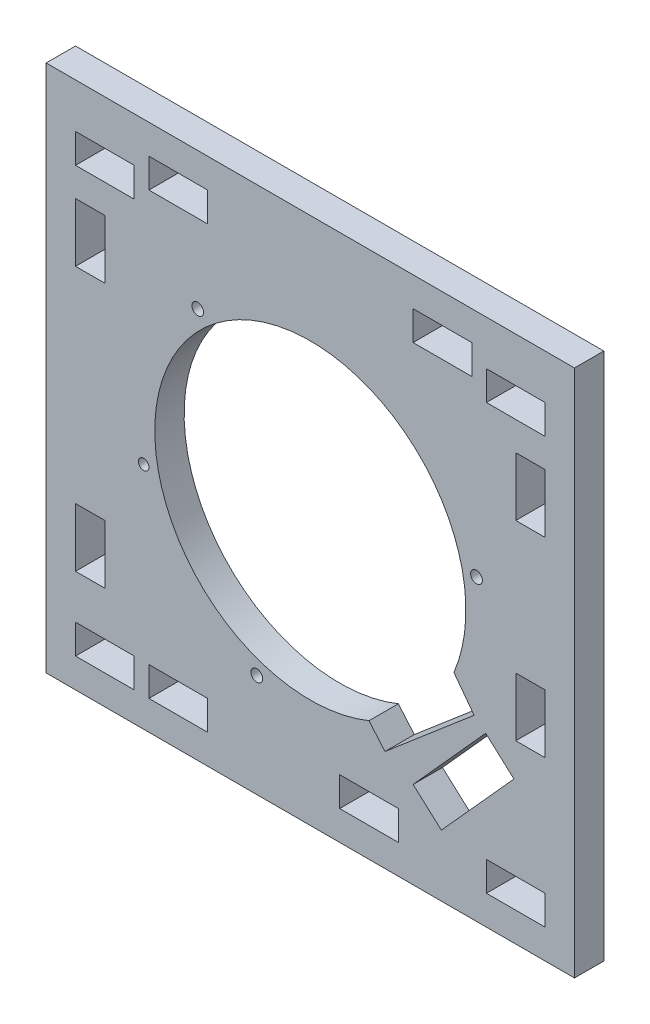
SolidWorks part; units mm, degrees
material "Balsa"
ref_plane "Plan de face" through (0, 0, 0) normal (0, 0, 1) x (1, 0, 0)
ref_plane "Plan de dessus" through (0, 0, 0) normal (0, 1, 0) x (1, 0, 0)
ref_plane "Plan de droite" through (0, 0, 0) normal (1, 0, 0) x (0, 0, -1)
sketch "Esquisse1" plane through (0, 0, 0) normal (0, 0, 1) x (1, 0, 0)
  line L0 (49.998, 15.0584) -> (52.714, 11.8706)
  line L1 (85, -5.4) -> (-5, -5.4)
  line L2 (85, -5.4) -> (85, 84.6)
  line L3 (85, 84.6) -> (-5, 84.6)
  line L4 (-5, -5.4) -> (-5, 84.6)
  line L6 (52.714, 11.8706) -> (67.9025, 24.8114)
  line L7 (67.9025, 24.8114) -> (64.4619, 29.4085)
  line L9 (57.5073, 9.4088) -> (69.8732, 23.1425)
  line L10 (69.8732, 23.1425) -> (74.6891, 18.8062)
  line L11 (74.6891, 18.8062) -> (62.3232, 5.0726)
  line L12 (62.3232, 5.0726) -> (57.5073, 9.4088)
  arc A0 (49.998, 15.0584) -> (64.4619, 29.4085) centre (40, 39.6) cw
  circle A1 centre (20.8169, 61.2152) radius 1
  circle A2 centre (68.3109, 45.4055) radius 1
  circle A3 centre (30.8722, 12.1793) radius 1
  circle A4 centre (11.6112, 33.6773) radius 0.9
  dimension "D1" = 90
  dimension "D2" = 90
  dimension "D5" = 26.5
  dimension "D3" = 45
  dimension "D4" = 45
extrude "Boss.-Extru.2" add sketch "Esquisse1" along normal blind 5
sketch "Esquisse2" plane through (0, 0, 0) normal (0, 0, -1) x (-1, 0, 0)
  line L0 (-40, 84.6) -> (-40, -5.4) construction
  line L1 (-80, 77) -> (-70, 77)
  line L2 (-80, 77) -> (-80, 72)
  line L3 (-80, 72) -> (-70, 72)
  line L4 (-70, 77) -> (-70, 72)
  line L5 (-10, 77) -> (-10, 72)
  line L6 (0, 72) -> (-10, 72)
  line L7 (0, 77) -> (0, 72)
  line L8 (0, 77) -> (-10, 77)
  line L9 (-85, 84.6) -> (5, 84.6) construction
  line L10 (5, -5.4) -> (-85, -5.4) construction
  line L11 (5, 39.6) -> (-85, 39.6) construction
  line L12 (5, 84.6) -> (5, -5.4) construction
  line L13 (-85, -5.4) -> (-85, 84.6) construction
  line L14 (-22.5, 74.6) -> (-22.5, 79.6)
  line L15 (-80, -0.4) -> (-70, -0.4)
  line L16 (-80, -0.4) -> (-80, 4.6)
  line L17 (-80, 4.6) -> (-70, 4.6)
  line L18 (-70, -0.4) -> (-70, 4.6)
  line L19 (-10, 4.6) -> (0, 4.6)
  line L20 (-10, 4.6) -> (-10, -0.4)
  line L21 (-10, -0.4) -> (0, -0.4)
  line L22 (0, 4.6) -> (0, -0.4)
  line L23 (-67.5, 74.6) -> (-57.5, 74.6)
  line L24 (-67.5, 74.6) -> (-67.5, 79.6)
  line L25 (-67.5, 79.6) -> (-57.5, 79.6)
  line L26 (-57.5, 74.6) -> (-57.5, 79.6)
  line L27 (-12.5, 79.6) -> (-22.5, 79.6)
  line L28 (-12.5, 74.6) -> (-12.5, 79.6)
  line L29 (-12.5, 74.6) -> (-22.5, 74.6)
  line L30 (-85, 84.6) -> (5, 84.6) construction
  line L31 (-5, 12.1) -> (-5, 22.1)
  line L32 (0, 67.1) -> (-5, 67.1)
  line L33 (0, 67.1) -> (0, 57.1)
  line L34 (0, 57.1) -> (-5, 57.1)
  line L35 (-5, 67.1) -> (-5, 57.1)
  line L36 (0, 22.1) -> (-5, 22.1)
  line L37 (0, 12.1) -> (0, 22.1)
  line L38 (0, 12.1) -> (-5, 12.1)
  line L39 (5, 84.6) -> (5, -5.4) construction
  line L40 (5, -5.4) -> (-85, -5.4) construction
  line L41 (-22.5, -0.4) -> (-12.5, -0.4)
  line L42 (-22.5, -0.4) -> (-22.5, 4.6)
  line L43 (-22.5, 4.6) -> (-12.5, 4.6)
  line L44 (-12.5, -0.4) -> (-12.5, 4.6)
  line L45 (-55, -0.4) -> (-45, -0.4)
  line L46 (-55, -0.4) -> (-55, 4.6)
  line L47 (-55, 4.6) -> (-45, 4.6)
  line L48 (-45, -0.4) -> (-45, 4.6)
  line L49 (-85, -5.4) -> (-85, 84.6) construction
  line L50 (-80, 57.1) -> (-75, 57.1)
  line L51 (-80, 57.1) -> (-80, 67.1)
  line L52 (-80, 67.1) -> (-75, 67.1)
  line L53 (-75, 57.1) -> (-75, 67.1)
  line L54 (-80, 34.6) -> (-75, 34.6)
  line L55 (-80, 34.6) -> (-80, 24.6)
  line L56 (-80, 24.6) -> (-75, 24.6)
  line L57 (-75, 34.6) -> (-75, 24.6)
  circle A4 centre (-40, 39.6) radius 40 construction
  dimension "D15" = 10
  dimension "D18" = 5
  dimension "D20" = 35
  dimension "D22" = 80
  dimension "D24" = 10
  dimension "D25" = 5
  dimension "D26" = 17.5
  dimension "D28" = 5
  dimension "D29" = 5
  dimension "D1" = 60
  dimension "D2" = 10
  dimension "D3" = 5
  dimension "D4" = 10
  dimension "D5" = 10
  dimension "D6" = 5
  dimension "D7" = 32.4
  dimension "D8" = 5
  dimension "D9" = 35
  dimension "D10" = 30
  dimension "D11" = 30
  dimension "D12" = 35
  dimension "D13" = 5
  dimension "D14" = 5
  dimension "D16" = 35
  dimension "D17" = 5
  dimension "D19" = 10
  dimension "D21" = 5
  dimension "D23" = 10
  dimension "D27" = 5
  dimension "D30" = 10
  dimension "D31" = 10
  dimension "D32" = 17.5
  dimension "D33" = 5
extrude "Créneaux -" cut sketch "Esquisse2" against normal blind 5
